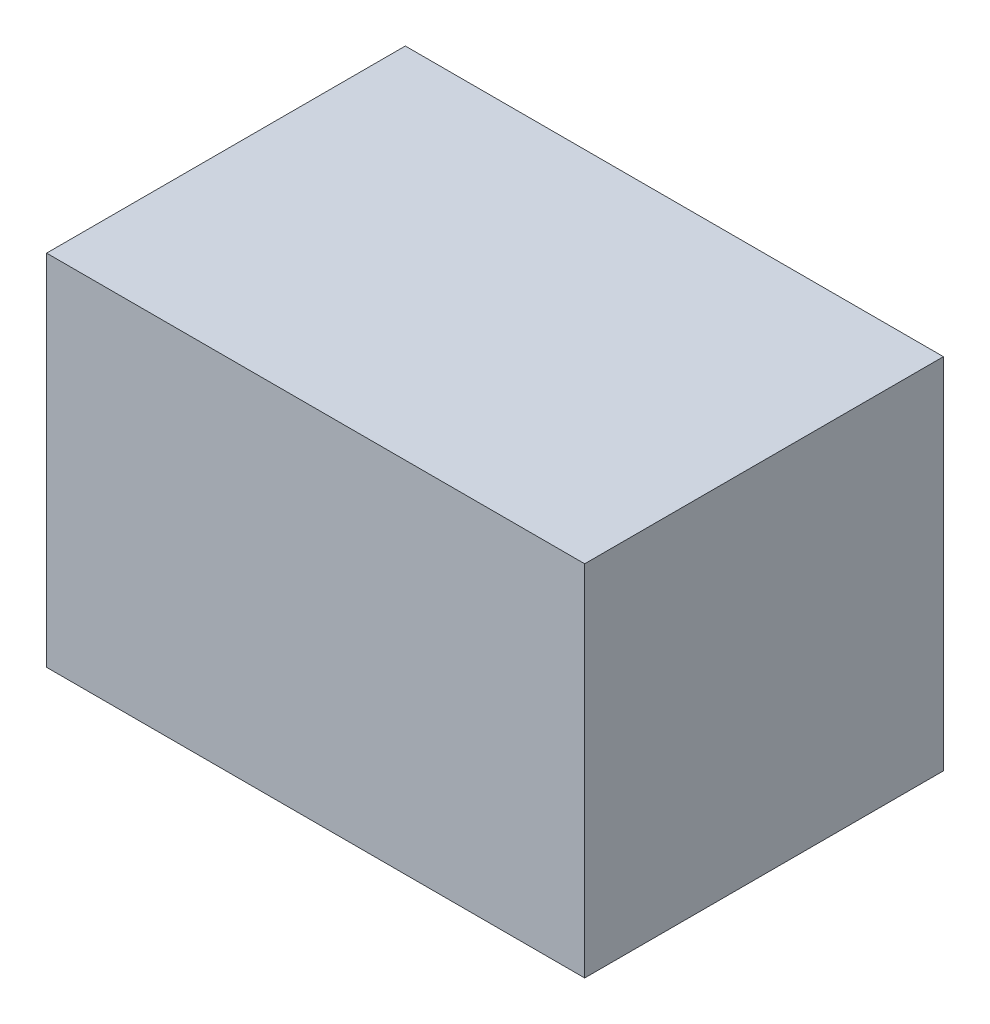
SolidWorks part; units mm, degrees
ref_plane "Front Plane" through (0, 0, 0) normal (0, 0, 1) x (1, 0, 0)
ref_plane "Top Plane" through (0, 0, 0) normal (0, 1, 0) x (1, 0, 0)
ref_plane "Right Plane" through (0, 0, 0) normal (1, 0, 0) x (0, 0, -1)
sketch "Sketch1" plane through (0, 0, 0) normal (0, 0, 1) x (1, 0, 0)
  line L1 (0, 0) -> (150, 0)
  line L2 (0, 0) -> (0, -100)
  line L3 (0, -100) -> (150, -100)
  line L4 (150, 0) -> (150, -100)
  dimension "D1" = 150
  dimension "D2" = 100
extrude "Boss-Extrude1" add sketch "Sketch1" along normal blind 100
